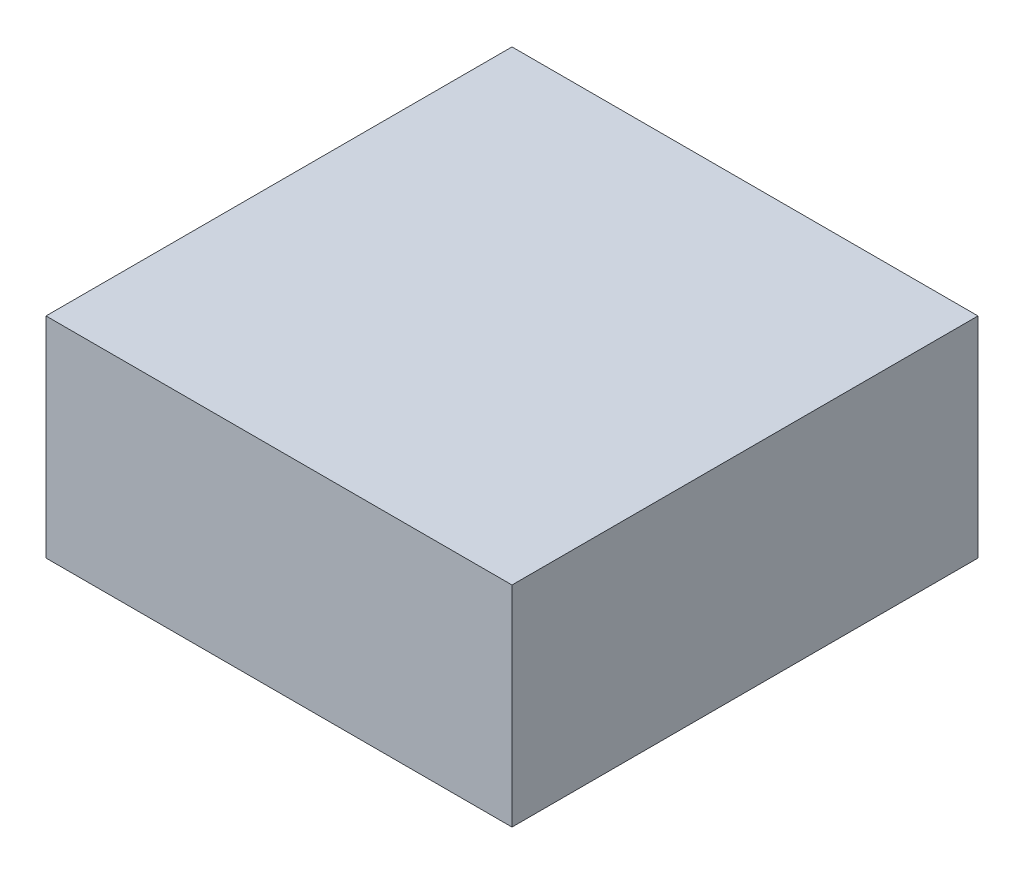
SolidWorks part; units mm, degrees
ref_plane "Plano frontal" through (0, 0, 0) normal (0, 0, 1) x (1, 0, 0)
ref_plane "Plano superior" through (0, 0, 0) normal (0, 1, 0) x (1, 0, 0)
ref_plane "Plano direito" through (0, 0, 0) normal (1, 0, 0) x (0, 0, -1)
sketch "Esboço1" plane through (0, 0, 0) normal (0, 1, 0) x (1, 0, 0)
  line L1 (-22.8675, 11.8124) -> (-2.8675, 11.8124)
  line L2 (-22.8675, 11.8124) -> (-22.8675, -8.1876)
  line L3 (-22.8675, -8.1876) -> (-2.8675, -8.1876)
  line L4 (-2.8675, 11.8124) -> (-2.8675, -8.1876)
extrude "Ressalto-extrusão1" add sketch "Esboço1" along normal blind 9
